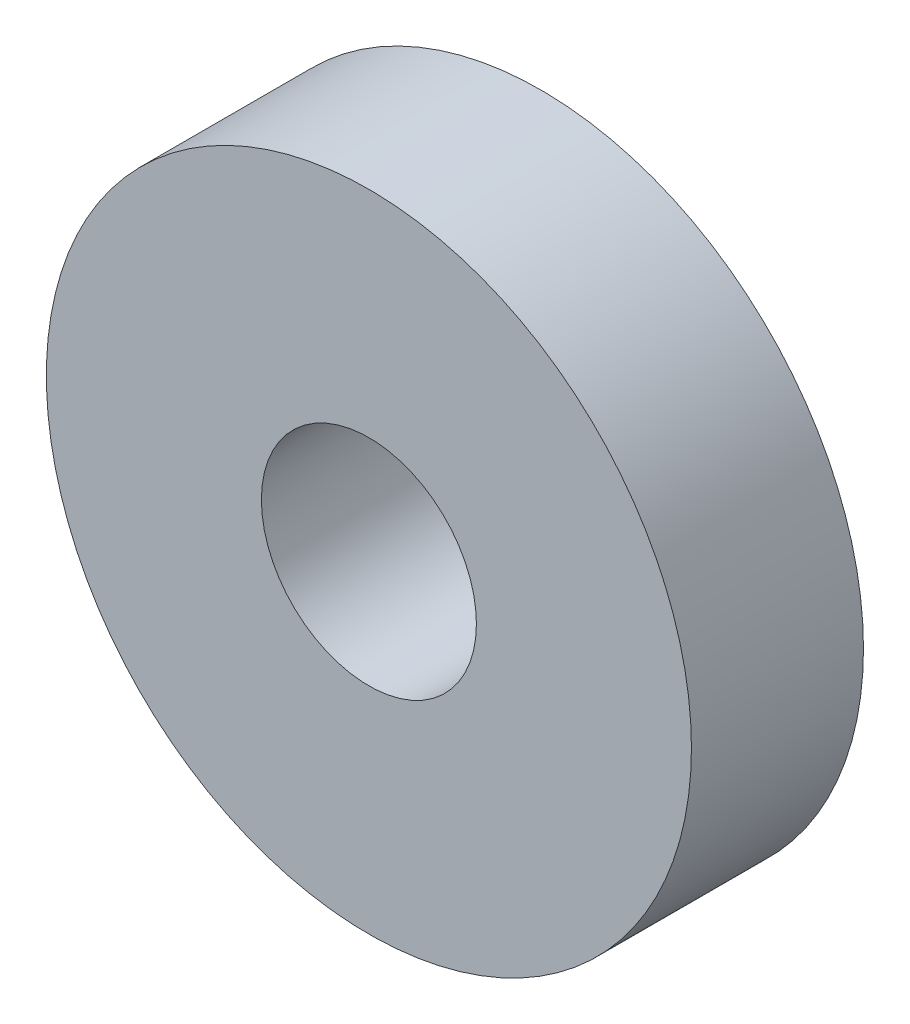
SolidWorks part; units mm, degrees
material "1.0503 (C45)"
ref_plane "前视基准面" through (0, 0, 0) normal (0, 0, 1) x (1, 0, 0)
ref_plane "上视基准面" through (0, 0, 0) normal (0, 1, 0) x (1, 0, 0)
ref_plane "右视基准面" through (0, 0, 0) normal (1, 0, 0) x (0, 0, -1)
other "Configuration Table"
sketch "草图2" plane through (0, 0, 0) normal (0, 0, 1) x (1, 0, 0)
  circle A0 centre (0, 0) radius 2.5
  circle A1 centre (0, 0) radius 7.5
  dimension "D1" = 5
  dimension "D2" = 15
extrude "凸台-拉伸1" add sketch "草图2" along normal blind 4
